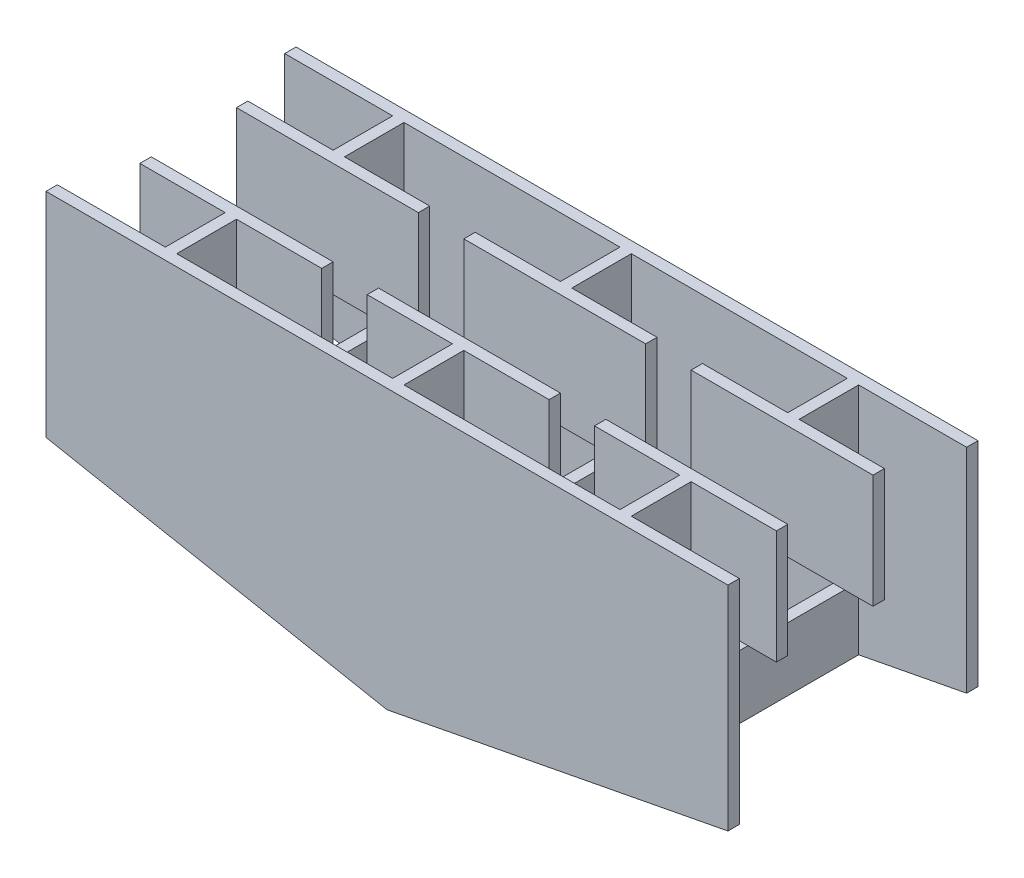
SolidWorks part; units mm, degrees
ref_plane "Front" through (0, 0, 0) normal (0, 0, 1) x (1, 0, 0)
ref_plane "Top" through (0, 0, 0) normal (0, 1, 0) x (1, 0, 0)
ref_plane "Right" through (0, 0, 0) normal (1, 0, 0) x (0, 0, -1)
sketch "Sketch1" plane through (0, 0, 0) normal (0, 0, 1) x (1, 0, 0)
  line L0 (-152.4, 62.23) -> (0, 62.23) construction
  line L1 (-152.4, -62.23) -> (152.4, -62.23) construction
  line L2 (-152.4, -62.23) -> (-152.4, 62.23) construction
  line L3 (-152.4, 62.23) -> (152.4, 62.23) construction
  line L4 (152.4, -62.23) -> (152.4, 62.23) construction
  line L5 (-152.4, -62.23) -> (152.4, 62.23) construction
  line L6 (-152.4, 62.23) -> (152.4, -62.23) construction
  line L7 (-152.4, 62.23) -> (-152.4, -33.02)
  line L8 (-152.4, -33.02) -> (0, -62.23)
  line L9 (0, -62.23) -> (152.4, -32.9764)
  line L10 (152.4, -32.9764) -> (152.4, 62.23)
  line L11 (152.4, 62.23) -> (-152.4, 62.23)
  point P0 (0, 0)
  dimension "D1" = 304.8
  dimension "D2" = 124.46
  dimension "D3" = 95.25
extrude "Boss-Extrude1" add sketch "Sketch1" against normal blind 111.76
ref_plane "Plane1" through (0, 0, -5.08) normal (0, 0, 1) x (1, 0, 0)
sketch "Sketch2" plane through (0, 0, 0) normal (0, 0, 1) x (1, 0, 0)
  line L0 (-152.4, -33.02) -> (-152.4, -13.97) construction
  line L1 (-152.4, 62.23) -> (-152.4, -33.02) construction
  line L2 (152.4, -32.9764) -> (152.4, 62.23) construction
  line L3 (-152.4, -13.97) -> (152.4, -13.97)
  line L4 (-152.4, -13.97) -> (-152.4, 11.43)
  line L5 (-152.4, 11.43) -> (152.4, 11.43)
  line L6 (152.4, -13.97) -> (152.4, 11.43)
  dimension "D1" = 19.05
  dimension "D2" = 25.4
sketch "Sketch5" plane through (0, 0, -5.08) normal (0, 0, 1) x (1, 0, 0)
  line L1 (-152.4, 11.43) -> (152.4, 11.43)
  line L2 (-152.4, 11.43) -> (-152.4, -13.97)
  line L3 (-152.4, -13.97) -> (152.4, -13.97)
  line L4 (152.4, 11.43) -> (152.4, -13.97)
  dimension "D1" = 19.05
  dimension "D2" = 25.4
extrude "Cut-Extrude3" cut sketch "Sketch5" against normal blind 101.6
sketch "Sketch3" plane through (0, 62.23, 0) normal (0, 1, 0) x (1, 0, 0)
  line L0 (152.4, 111.76) -> (-152.4, 111.76) construction
  line L1 (-2.54, 5.08) -> (-99.06, 5.08)
  line L2 (-2.54, 5.08) -> (-2.54, 106.68)
  line L3 (-2.54, 106.68) -> (-99.06, 106.68)
  line L4 (-99.06, 5.08) -> (-99.06, 106.68)
  line L5 (152.4, 0) -> (-152.4, 0) construction
  line L6 (0, 0) -> (0, 111.76) construction
  line L7 (2.54, 106.68) -> (99.06, 106.68)
  line L8 (99.06, 5.08) -> (99.06, 106.68)
  line L9 (2.54, 5.08) -> (99.06, 5.08)
  line L10 (2.54, 5.08) -> (2.54, 106.68)
  line L11 (-152.4, 111.76) -> (-152.4, 0) construction
  line L12 (-104.14, 106.68) -> (-152.4, 106.68)
  line L13 (-104.14, 106.68) -> (-104.14, 5.08)
  line L14 (-104.14, 5.08) -> (-152.4, 5.08)
  line L15 (-152.4, 106.68) -> (-152.4, 5.08)
  line L16 (104.14, 5.08) -> (152.4, 5.08)
  line L17 (152.4, 106.68) -> (152.4, 5.08)
  line L18 (104.14, 106.68) -> (152.4, 106.68)
  line L19 (104.14, 106.68) -> (104.14, 5.08)
  dimension "D1" = 2.54
  dimension "D2" = 96.52
  dimension "D3" = 5.08
  dimension "D4" = 5.08
  dimension "D5" = 5.08
  dimension "D6" = 5.08
  dimension "D7" = 5.08
extrude "Cut-Extrude4" cut sketch "Sketch3" against normal through all both and the other way through all
sketch "Sketch6" plane through (-104.14, 0, 0) normal (-1, 0, 0) x (0, 0, 1)
  line L0 (-5.08, 11.43) -> (-106.68, 11.43) construction
  line L1 (-74.9821, 11.43) -> (-36.8821, 11.43)
  line L2 (-74.9821, 11.43) -> (-74.9821, 62.23)
  line L3 (-74.9821, 62.23) -> (-36.8821, 62.23)
  line L4 (-36.8821, 11.43) -> (-36.8821, 62.23)
  line L5 (-5.08, 62.23) -> (-106.68, 62.23) construction
  dimension "D1" = 38.1
extrude "Cut-Extrude5" cut sketch "Sketch6" against normal up to surface (208.28 mm away) up to face at (104.14, 36.83, -55.88)
ref_plane "Plane2" through (0, 0, -36.8821) normal (0, 0, -1) x (-1, 0, 0)
sketch "Sketch7" plane through (0, 0, -36.8821) normal (0, 0, -1) x (-1, 0, 0)
  line L1 (-40.64, 62.23) -> (40.64, 62.23)
  line L2 (-40.64, 62.23) -> (-40.64, 11.43)
  line L3 (-40.64, 11.43) -> (40.64, 11.43)
  line L4 (40.64, 62.23) -> (40.64, 11.43)
  line L5 (60.96, 62.23) -> (142.24, 62.23)
  line L6 (60.96, 62.23) -> (60.96, 11.43)
  line L7 (60.96, 11.43) -> (142.24, 11.43)
  line L8 (142.24, 62.23) -> (142.24, 11.43)
  line L9 (-142.24, 62.23) -> (-60.96, 62.23)
  line L10 (-142.24, 62.23) -> (-142.24, 11.43)
  line L11 (-142.24, 11.43) -> (-60.96, 11.43)
  line L12 (-60.96, 62.23) -> (-60.96, 11.43)
  dimension "D1" = 38.1
  dimension "D2" = 38.1
  dimension "D3" = 38.1
  dimension "D4" = 38.1
  dimension "D5" = 38.1
  dimension "D6" = 38.1
extrude "Boss-Extrude2" add sketch "Sketch7" against normal blind 5.08
ref_plane "Plane3" through (0, 0, -55.9321) normal (0, 0, -1) x (-1, 0, 0)
mirror "Mirror1" about plane through (0, 0, -55.9321) normal (0, 0, -1) of "Boss-Extrude2"
